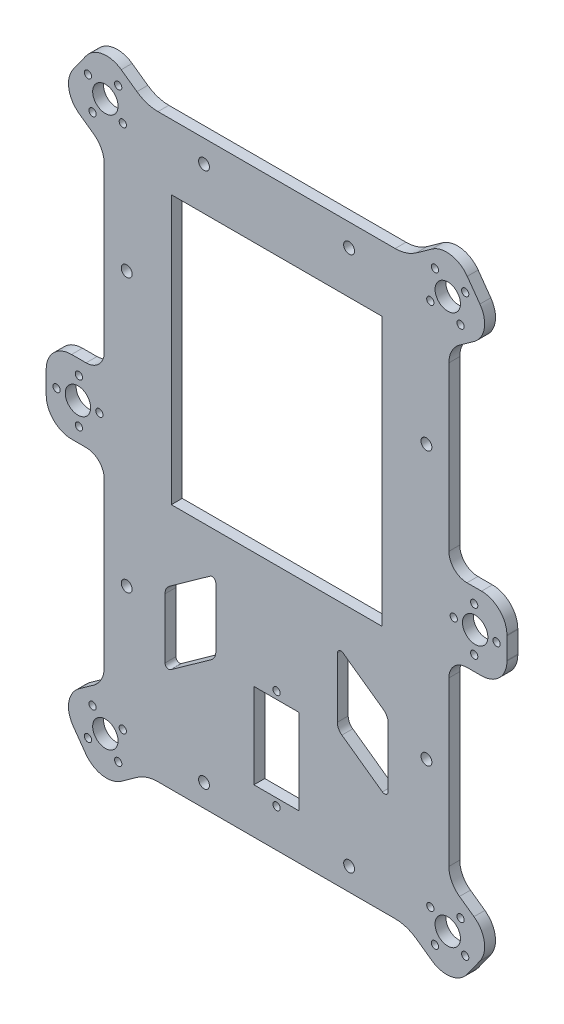
SolidWorks part; units mm, degrees
ref_plane "Front Plane" through (0, 0, 0) normal (0, 0, 1) x (1, 0, 0)
ref_plane "Top Plane" through (0, 0, 0) normal (0, 1, 0) x (1, 0, 0)
ref_plane "Right Plane" through (0, 0, 0) normal (1, 0, 0) x (0, 0, -1)
sketch "Sketch1" plane through (0, 0, 0) normal (0, 0, 1) x (1, 0, 0)
  line L0 (-15.0049, -75.172) -> (43, -75.172)
  line L1 (-24.4982, 18.6863) -> (-28.8129, 21.7633)
  line L2 (-42.0602, 15.2434) -> (-38.5765, 20.1284)
  line L3 (-36.4405, 2.638) -> (-40.4254, 5.4798)
  line L4 (-33.5049, -3.0612) -> (-33.5049, -48.0612)
  line L5 (-42.5049, -53.0612) -> (-38.5049, -53.0612)
  line L6 (-15.0049, -1.172) -> (-15.0049, -75.172)
  line L7 (-49.5003, -60.2356) -> (-49.5003, -66.1084)
  line L8 (-49.5049, -60.0612) -> (-49.5003, -60.2356)
  line L9 (46.6871, 16.828) -> (-18.692, 16.828)
  line L10 (77.5, -60.0612) -> (77.4954, -60.2356)
  line L11 (77.4954, -60.2356) -> (77.4954, -66.1084)
  line L12 (70.5, -53.0612) -> (66.5, -53.0612)
  line L13 (61.5, -3.0612) -> (61.5, -48.0612)
  line L14 (64.4356, 2.638) -> (68.4204, 5.4798)
  line L15 (70.0553, 15.2434) -> (66.5716, 20.1284)
  line L16 (52.4933, 18.6863) -> (56.808, 21.7633)
  line L17 (43, -1.172) -> (43, -75.172)
  line L18 (52.4933, -145.0303) -> (56.808, -148.1073)
  line L19 (70.0553, -141.5874) -> (66.5716, -146.4724)
  line L20 (64.4356, -128.9821) -> (68.4204, -131.8238)
  line L21 (61.5, -123.2828) -> (61.5, -78.2828)
  line L22 (70.5, -73.2828) -> (66.5, -73.2828)
  line L23 (77.5, -66.2828) -> (77.4954, -66.1084)
  line L24 (46.6871, -143.172) -> (-18.692, -143.172)
  line L25 (-49.5049, -66.2828) -> (-49.5003, -66.1084)
  line L26 (-42.5049, -73.2828) -> (-38.5049, -73.2828)
  line L27 (-33.5049, -123.2828) -> (-33.5049, -78.2828)
  line L28 (-36.4405, -128.9821) -> (-40.4254, -131.8238)
  line L29 (-42.0602, -141.5874) -> (-38.5765, -146.4724)
  line L30 (-24.4982, -145.0303) -> (-28.8129, -148.1073)
  line L32 (43, -1.172) -> (-15.0049, -1.172)
  line L33 (20.2475, -130.6739) -> (7.7475, -130.6739)
  line L34 (32.005, -106.6802) -> (43.1675, -114.6534)
  line L35 (7.7475, -130.6739) -> (7.7475, -107.1739)
  line L36 (7.7475, -107.1739) -> (20.2475, -107.1739)
  line L37 (20.2475, -107.1739) -> (20.2475, -130.6739)
  line L38 (32.33, -86.9123) -> (43.4925, -94.8855)
  line L39 (30.7487, -100.7828) -> (30.7487, -104.239)
  line L40 (44.7487, -100.7828) -> (44.7487, -113.8396)
  line L41 (-2.7537, -100.7828) -> (-2.7537, -87.726)
  line L42 (-16.7537, -100.7828) -> (-16.7537, -97.3267)
  line L43 (-16.7537, -100.7828) -> (-16.7537, -113.8396)
  line L44 (-2.7537, -100.7828) -> (-2.7537, -104.239)
  line L45 (-4.3349, -86.9123) -> (-15.4974, -94.8855)
  line L46 (-4.01, -106.6802) -> (-15.1724, -114.6534)
  line L47 (44.7487, -100.7828) -> (44.7487, -97.3267)
  line L48 (30.7487, -100.7828) -> (30.7487, -87.726)
  circle A0 centre (-37.998, 16.0311) radius 1
  circle A1 centre (-29.6584, 17.5638) radius 1
  circle A2 centre (-36.7303, 7.6471) radius 1
  arc A3 (-38.5049, -53.0612) -> (-33.5049, -48.0612) centre (-38.5049, -48.0612) ccw
  arc A4 (-49.5049, -60.0612) -> (-42.5049, -53.0612) centre (-42.5049, -60.0612) cw
  circle A5 centre (-28.3907, 9.1798) radius 1
  circle A6 centre (-33.1943, 12.6054) radius 3.5
  arc A7 (-24.4982, 18.6863) -> (-18.692, 16.828) centre (-18.692, 26.828) ccw
  arc A8 (-40.4254, 5.4798) -> (-42.0602, 15.2434) centre (-36.361, 11.179) cw
  arc A9 (-38.5765, 20.1284) -> (-28.8129, 21.7633) centre (-32.8773, 16.0641) cw
  arc A10 (-33.5049, -3.0612) -> (-36.4405, 2.638) centre (-40.5049, -3.0612) ccw
  arc A11 (61.5, -3.0612) -> (64.4356, 2.638) centre (68.5, -3.0612) cw
  arc A12 (66.5716, 20.1284) -> (56.808, 21.7633) centre (60.8724, 16.0641) ccw
  arc A13 (68.4204, 5.4798) -> (70.0553, 15.2434) centre (64.3561, 11.179) ccw
  arc A14 (52.4933, 18.6863) -> (46.6871, 16.828) centre (46.6871, 26.828) cw
  circle A15 centre (61.1894, 12.6054) radius 3.5
  circle A16 centre (56.3858, 9.1798) radius 1
  arc A17 (77.5, -60.0612) -> (70.5, -53.0612) centre (70.5, -60.0612) ccw
  arc A18 (66.5, -53.0612) -> (61.5, -48.0612) centre (66.5, -48.0612) cw
  circle A19 centre (64.7254, 7.6471) radius 1
  circle A20 centre (57.6534, 17.5638) radius 1
  circle A21 centre (65.9931, 16.0311) radius 1
  circle A22 centre (65.9931, -142.3751) radius 1
  circle A23 centre (57.6534, -143.9078) radius 1
  circle A24 centre (64.7254, -133.9911) radius 1
  arc A25 (66.5, -73.2828) -> (61.5, -78.2828) centre (66.5, -78.2828) ccw
  arc A26 (77.5, -66.2828) -> (70.5, -73.2828) centre (70.5, -66.2828) cw
  circle A27 centre (56.3858, -135.5238) radius 1
  circle A28 centre (61.1894, -138.9495) radius 3.5
  arc A29 (52.4933, -145.0303) -> (46.6871, -143.172) centre (46.6871, -153.172) ccw
  arc A30 (68.4204, -131.8238) -> (70.0553, -141.5874) centre (64.3561, -137.523) cw
  arc A31 (66.5716, -146.4724) -> (56.808, -148.1073) centre (60.8724, -142.4081) cw
  arc A32 (61.5, -123.2828) -> (64.4356, -128.9821) centre (68.5, -123.2828) ccw
  arc A33 (-33.5049, -123.2828) -> (-36.4405, -128.9821) centre (-40.5049, -123.2828) cw
  arc A34 (-38.5765, -146.4724) -> (-28.8129, -148.1073) centre (-32.8773, -142.4081) ccw
  arc A35 (-40.4254, -131.8238) -> (-42.0602, -141.5874) centre (-36.361, -137.523) ccw
  arc A36 (-24.4982, -145.0303) -> (-18.692, -143.172) centre (-18.692, -153.172) cw
  circle A37 centre (-33.1943, -138.9495) radius 3.5
  circle A38 centre (-28.3907, -135.5238) radius 1
  arc A39 (-49.5049, -66.2828) -> (-42.5049, -73.2828) centre (-42.5049, -66.2828) ccw
  arc A40 (-38.5049, -73.2828) -> (-33.5049, -78.2828) centre (-38.5049, -78.2828) cw
  circle A41 centre (-36.7303, -133.9911) radius 1
  circle A42 centre (-29.6584, -143.9078) radius 1
  circle A43 centre (-37.998, -142.3751) radius 1
  circle A45 centre (55.31, -25.5612) radius 1.5
  circle A46 centre (33.9975, -136.982) radius 1.5
  circle A47 centre (-6.0025, -136.982) radius 1.5
  circle A48 centre (-6.0025, 10.638) radius 1.5
  circle A49 centre (33.9975, 10.638) radius 1.5
  circle A50 centre (13.9975, -132.6739) radius 1
  circle A51 centre (13.9975, -105.1739) radius 1
  arc A52 (-16.7537, -97.3267) -> (-15.4974, -94.8855) centre (-13.7537, -97.3267) cw
  arc A53 (-2.7537, -104.239) -> (-4.01, -106.6802) centre (-5.7537, -104.239) cw
  arc A54 (-15.1724, -114.6534) -> (-16.7537, -113.8396) centre (-15.7537, -113.8396) cw
  arc A55 (-2.7537, -87.726) -> (-4.3349, -86.9123) centre (-3.7537, -87.726) ccw
  arc A56 (30.7487, -87.726) -> (32.33, -86.9123) centre (31.7487, -87.726) cw
  arc A57 (43.1675, -114.6534) -> (44.7487, -113.8396) centre (43.7487, -113.8396) ccw
  arc A58 (30.7487, -104.239) -> (32.005, -106.6802) centre (33.7487, -104.239) ccw
  arc A59 (44.7487, -97.3267) -> (43.4925, -94.8855) centre (41.7487, -97.3267) ccw
  circle A60 centre (-27.3149, -25.5612) radius 1.5
  circle A61 centre (55.31, -100.7828) radius 1.5
  circle A62 centre (-27.3149, -100.7828) radius 1.5
  circle A74 centre (-40.7503, -63.172) radius 3.5
  circle A75 centre (-46.6503, -63.172) radius 1
  circle A76 centre (-34.8503, -63.172) radius 1
  circle A77 centre (-40.4873, -69.2563) radius 1
  circle A78 centre (-40.4873, -57.0877) radius 1
  circle A79 centre (68.4824, -57.0877) radius 1
  circle A80 centre (68.4824, -69.2563) radius 1
  circle A81 centre (62.8454, -63.172) radius 1
  circle A82 centre (74.6454, -63.172) radius 1
  circle A83 centre (68.7454, -63.172) radius 3.5
  point P25 (-34.5122, 25.8276)
  point P29 (-34.5122, 25.8276)
  point P64 (62.5072, 25.8276)
  point P95 (62.5072, -152.1716)
  point P124 (-34.5122, -152.1716)
  dimension "D6" = 3
  dimension "D7" = 1
  dimension "D1" = 10
  dimension "D2" = 7
  dimension "D3" = 7
  dimension "D4" = 5
  dimension "D5" = 7
extrude "Бобышка-Вытянуть1" add sketch "Sketch1" against normal blind 3
